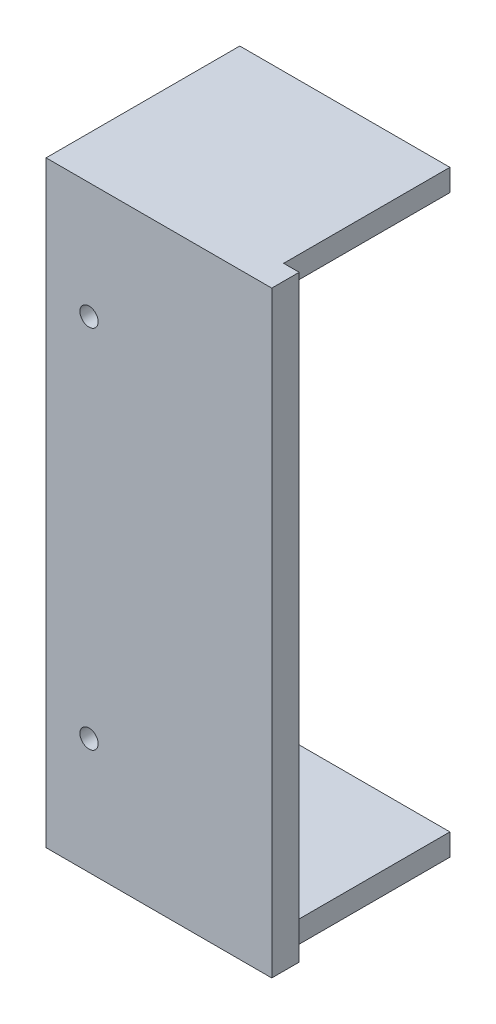
SolidWorks part; units mm, degrees
ref_plane "Front Plane" through (0, 0, 0) normal (0, 0, 1) x (1, 0, 0)
ref_plane "Top Plane" through (0, 0, 0) normal (0, 1, 0) x (1, 0, 0)
ref_plane "Right Plane" through (0, 0, 0) normal (1, 0, 0) x (0, 0, -1)
ref_plane "Plane_Z+352.00" through (0, 0, 352) normal (0, 0, 1) x (1, 0, 0)
sketch "Sketch1" plane through (0, 0, 352) normal (0, 0, 1) x (1, 0, 0)
  line L0 (-94.7, -32.7) -> (-71.7, -32.7)
  line L1 (-71.7, -32.7) -> (-71.7, -30.3)
  line L2 (-71.7, -30.3) -> (-92.3, -30.3)
  line L3 (-92.3, -30.3) -> (-92.3, 30.3)
  line L4 (-92.3, 30.3) -> (-71.7, 30.3)
  line L5 (-71.7, 30.3) -> (-71.7, 32.7)
  line L6 (-71.7, 32.7) -> (-94.7, 32.7)
  line L7 (-94.7, 32.7) -> (-94.7, -32.7)
extrude "U_skirt" add sketch "Sketch1" along normal blind 18.2
ref_plane "Plane_Z+370.20" through (0, 0, 370.2) normal (0, 0, 1) x (1, 0, 0)
sketch "Sketch2" plane through (0, 0, 370.2) normal (0, 0, 1) x (1, 0, 0)
  line L0 (-94.7, -32.7) -> (-70, -32.7)
  line L1 (-70, -32.7) -> (-70, 32.7)
  line L2 (-70, 32.7) -> (-94.7, 32.7)
  line L3 (-94.7, 32.7) -> (-94.7, -32.7)
extrude "Top_plate" add sketch "Sketch2" along normal blind 3
sketch "Sketch3" plane through (0, 0, 370.2) normal (0, 0, 1) x (1, 0, 0)
  circle A0 centre (-90, 20) radius 1
  circle A1 centre (-90, -20) radius 1
extrude "Filament_pin_holes" cut sketch "Sketch3" against normal through all and the other way through all
